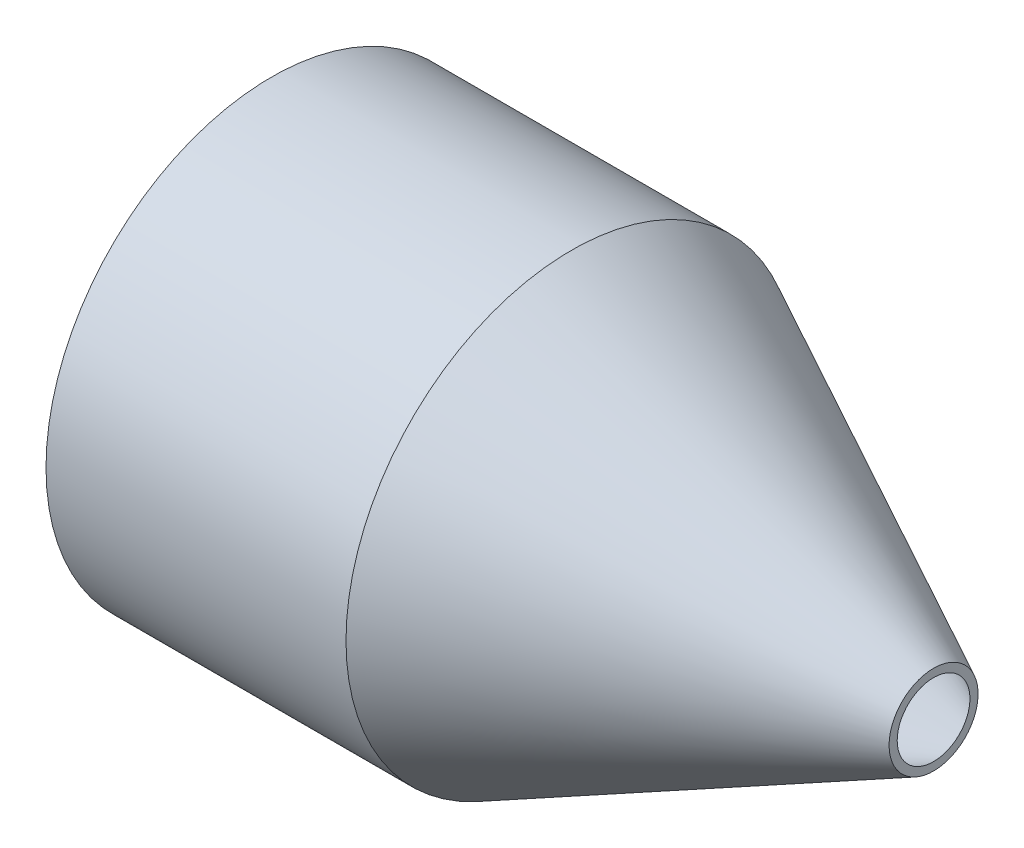
SolidWorks part; units mm, degrees
ref_plane "Спереди" through (0, 0, 0) normal (0, 0, 1) x (1, 0, 0)
ref_plane "Сверху" through (0, 0, 0) normal (0, 1, 0) x (1, 0, 0)
ref_plane "Справа" through (0, 0, 0) normal (1, 0, 0) x (0, 0, -1)
sketch "Эскиз1" plane through (0, 0, 0) normal (0, 0, 1) x (1, 0, 0)
  line L0 (0, 0) -> (-74.3959, 0) construction
  line L1 (16.5574, 300) -> (416.5574, 300)
  line L2 (416.5574, 300) -> (916.5574, 50)
  line L3 (16.5574, 310) -> (418.9181, 310)
  line L4 (418.9181, 310) -> (916.5574, 61.1803)
  line L6 (916.5574, 50) -> (916.5574, 61.1803)
  line L7 (418.9181, 310) -> (921.0296, 58.9443) construction
  line L8 (16.5574, 300) -> (16.5574, 0)
  line L9 (16.5574, 0) -> (6.5574, 0)
  line L10 (6.5574, 0) -> (6.5574, 310)
  line L11 (6.5574, 310) -> (16.5574, 310)
  dimension "D1" = 600
  dimension "D2" = 400
  dimension "D3" = 100
  dimension "D4" = 500
  dimension "D6" = 10
  dimension "D5" = 10
revolve "Повернуть1" add sketch "Эскиз1" angle 360 about L0
